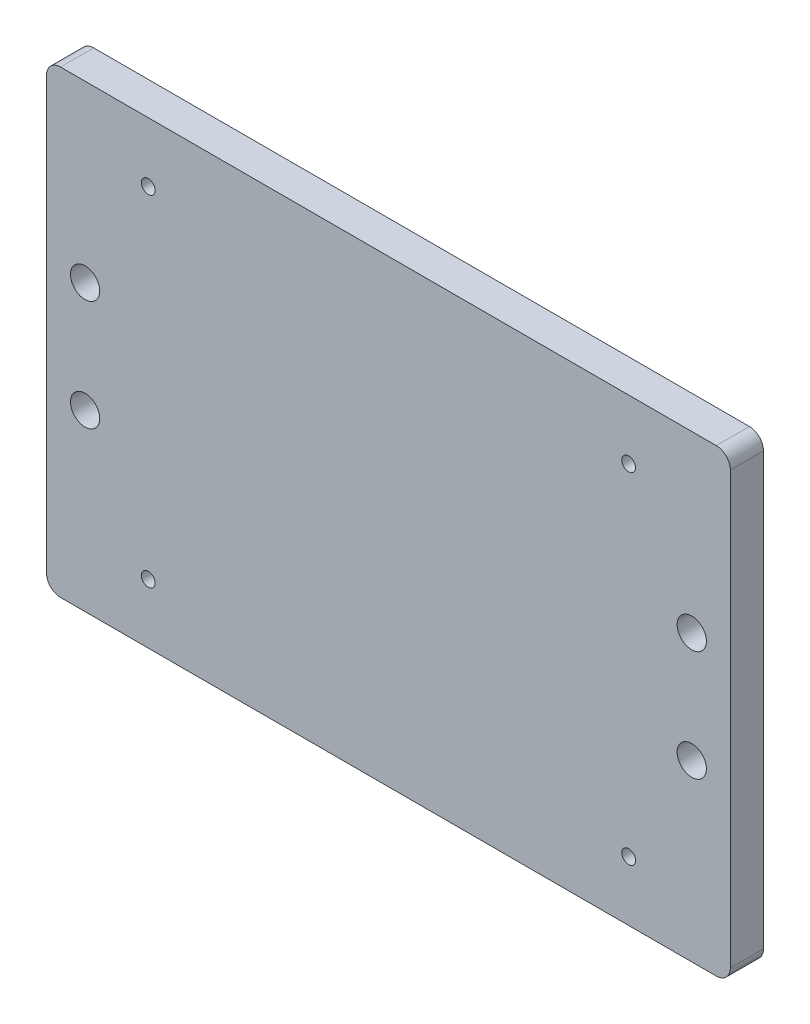
SolidWorks part; units mm, degrees
ref_plane "Front Plane" through (0, 0, 0) normal (0, 0, 1) x (1, 0, 0)
ref_plane "Top Plane" through (0, 0, 0) normal (0, 1, 0) x (1, 0, 0)
ref_plane "Right Plane" through (0, 0, 0) normal (1, 0, 0) x (0, 0, -1)
other "Configuration Table"
ref_plane "Plane1" through (0, 0, -12) normal (0, 0, -1) x (-1, 0, 0)
sketch "Sketch1" plane through (0, 0, -12) normal (0, 0, -1) x (-1, 0, 0)
  line L0 (-495.554, 344.3605) -> (-371.729, 344.3605) construction
  line L1 (-493.014, 385.953) -> (-374.269, 385.953)
  line L2 (-495.554, 383.413) -> (-495.554, 305.308)
  line L3 (-493.014, 302.768) -> (-374.269, 302.768)
  line L4 (-433.6415, 354.3605) -> (-433.6415, 344.3605) construction
  line L5 (-433.6415, 344.3605) -> (-433.6415, 334.3605) construction
  line L6 (-482.569, 354.3605) -> (-481.584, 354.3605) construction
  line L7 (-495.554, 354.3605) -> (-494.569, 354.3605) construction
  line L20 (-371.729, 383.413) -> (-371.729, 305.308)
  line L21 (-495.554, 354.3605) -> (-371.729, 354.3605) construction
  line L22 (-371.729, 334.3605) -> (-495.554, 334.3605) construction
  line L23 (-388.239, 309.118) -> (-479.044, 309.118) construction
  line L24 (-481.584, 311.658) -> (-481.584, 377.063) construction
  line L25 (-495.554, 354.3605) -> (-488.569, 354.3605) construction
  line L26 (-488.569, 354.3605) -> (-495.554, 354.3605) construction
  line L27 (-385.699, 377.063) -> (-385.699, 311.658) construction
  line L28 (-479.044, 379.603) -> (-388.239, 379.603) construction
  line L29 (-385.699, 311.658) -> (-385.699, 377.063) construction
  line L30 (-388.239, 379.603) -> (-479.044, 379.603) construction
  line L31 (-481.584, 377.063) -> (-481.584, 311.658) construction
  line L32 (-479.044, 309.118) -> (-388.239, 309.118) construction
  line L33 (-384.714, 354.3605) -> (-385.699, 354.3605) construction
  line L34 (-372.714, 354.3605) -> (-371.729, 354.3605) construction
  arc A0 (-481.584, 311.658) -> (-479.044, 309.118) centre (-479.044, 311.658) ccw construction
  circle A1 centre (-477.139, 313.563) radius 1.575 construction
  circle A2 centre (-390.144, 313.563) radius 1.575 construction
  arc A3 (-388.239, 309.118) -> (-385.699, 311.658) centre (-388.239, 311.658) ccw construction
  circle A4 centre (-390.144, 375.158) radius 1.575 construction
  arc A5 (-479.044, 379.603) -> (-481.584, 377.063) centre (-479.044, 377.063) ccw construction
  circle A6 centre (-477.139, 375.158) radius 1.575 construction
  arc A7 (-385.699, 377.063) -> (-388.239, 379.603) centre (-388.239, 377.063) ccw construction
  circle A20 centre (-477.139, 313.563) radius 1.575 construction
  circle A26 centre (-488.569, 354.3605) radius 6 construction
  circle A27 centre (-488.569, 334.3605) radius 6 construction
  circle A28 centre (-378.714, 334.3605) radius 6 construction
  circle A29 centre (-378.714, 354.3605) radius 6 construction
  arc A30 (-374.269, 385.953) -> (-371.729, 383.413) centre (-374.269, 383.413) cw
  arc A31 (-374.269, 302.768) -> (-371.729, 305.308) centre (-374.269, 305.308) ccw
  arc A32 (-495.554, 305.308) -> (-493.014, 302.768) centre (-493.014, 305.308) ccw
  arc A33 (-493.014, 385.953) -> (-495.554, 383.413) centre (-493.014, 383.413) ccw
  arc A49 (-388.239, 309.118) -> (-385.699, 311.658) centre (-388.239, 311.658) ccw construction
  arc A50 (-385.699, 377.063) -> (-388.239, 379.603) centre (-388.239, 377.063) ccw construction
  arc A51 (-479.044, 379.603) -> (-481.584, 377.063) centre (-479.044, 377.063) ccw construction
  arc A52 (-481.584, 311.658) -> (-479.044, 309.118) centre (-479.044, 311.658) ccw construction
  point P60 (-472.7513, 314.4336)
  point P62 (-477.139, 313.563)
  point P86 (-477.139, 375.158)
  point P88 (-390.144, 375.158)
  point P90 (-390.144, 313.563)
  dimension "D3" = 12
  dimension "D8" = 2.54
  dimension "D12" = 6.35
  dimension "D13" = 6.35
  dimension "D14" = 20
  dimension "D15" = 13.97
extrude "Boss-Extrude1" add sketch "Sketch1" along normal blind 6
hole_wizard "M5 Clearance Hole1" positions "Sketch3" profile "Sketch4" hole size "M5" standard "ANSI Metric" end condition through all
sketch "Sketch3" plane through (0, 0, -18) normal (0, 0, -1) x (-1, 0, 0)
  point P0 (-488.569, 354.3605)
  point P3 (-488.569, 334.3605)
  point P6 (-378.714, 334.3605)
  point P9 (-378.714, 354.3605)
sketch "Sketch4" plane through (488.569, 354.3605, -18) normal (1, 0, 0) x (0, 1, 0)
  line L0 (0, 0) -> (0, 6)
  line L1 (0, 6) -> (2.65, 6)
  line L2 (2.65, 6) -> (2.65, 0)
  line L5 (2.65, 0) -> (0, 0)
  line L11 (0, -6.35) -> (0, 107.95) construction
  dimension "Thru Hole Dia." = 5.3
  dimension "Thru Hole Depth" = 6
hole_wizard "M3x0.5 Tapped Hole1" positions "Sketch5" profile "Sketch6" tap size "M3x0.5" standard "ANSI Metric" end condition through all
sketch "Sketch5" plane through (0, 0, -18) normal (0, 0, -1) x (-1, 0, 0)
  point P15 (-477.139, 375.158)
  point P18 (-390.144, 375.158)
  point P21 (-390.144, 313.563)
  point P24 (-477.139, 313.563)
sketch "Sketch6" plane through (477.139, 375.158, -18) normal (1, 0, 0) x (0, 1, 0)
  line L0 (0, 0) -> (0, 6)
  line L1 (0, 6) -> (1.25, 6)
  line L2 (1.25, 6) -> (1.25, 0)
  line L5 (1.25, 0) -> (0, 0)
  line L11 (0, -6.35) -> (0, 107.95) construction
  dimension "Thru Tap Drill Dia." = 2.5
  dimension "Thru Tap Drill Depth" = 6
cosmetic thread "Hole Thread5" parameters "D2"=3
cosmetic thread "Hole Thread6" parameters "D2"=3
cosmetic thread "Hole Thread7" parameters "D2"=3
cosmetic thread "Hole Thread8" parameters "D2"=3
equation "\"D14@Sketch1\"=20mm"
